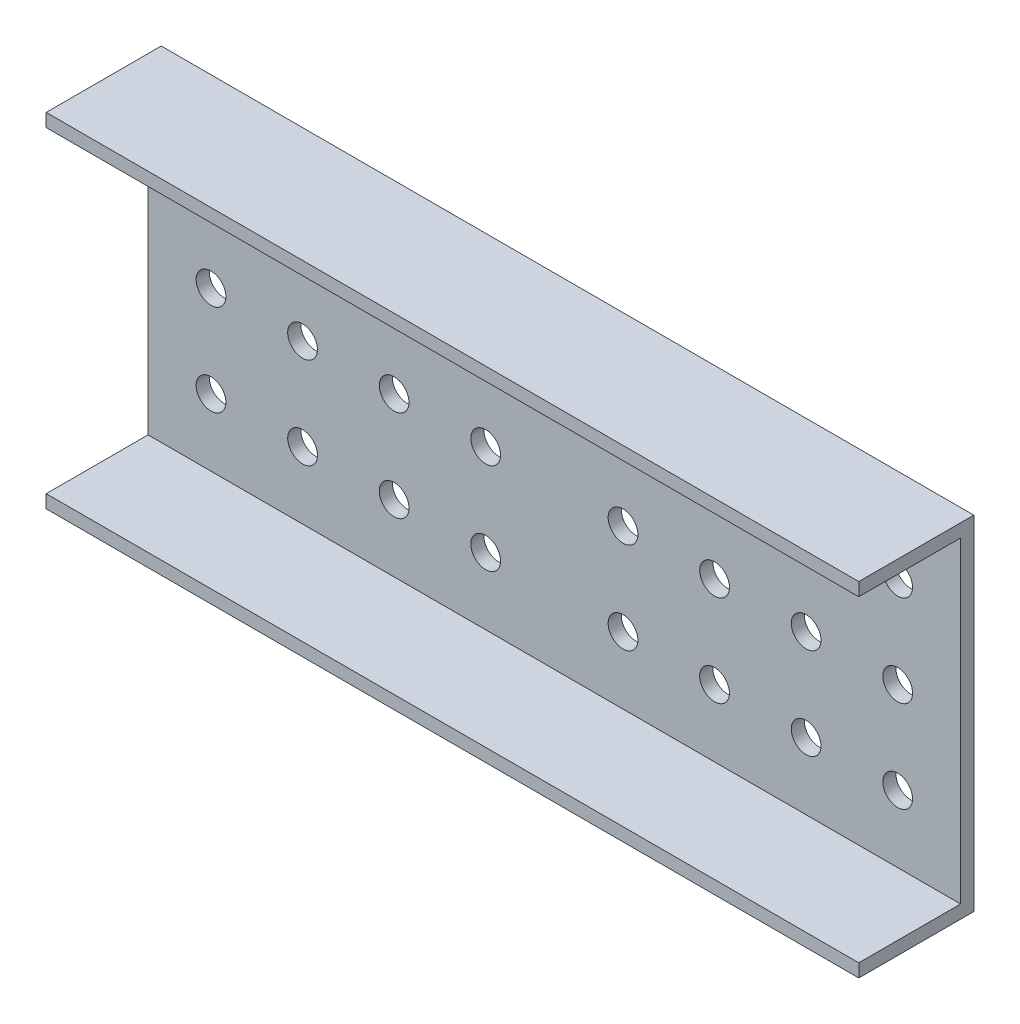
SolidWorks part; units mm, degrees
ref_plane "前视基准面" through (0, 0, 0) normal (0, 0, 1) x (1, 0, 0)
ref_plane "上视基准面" through (0, 0, 0) normal (0, 1, 0) x (1, 0, 0)
ref_plane "右视基准面" through (0, 0, 0) normal (1, 0, 0) x (0, 0, -1)
sketch "草图1" plane through (0, 0, 0) normal (0, 0, 1) x (1, 0, 0)
  line L1 (-355, 150) -> (355, 150)
  line L2 (-355, 150) -> (-355, -150)
  line L3 (-355, -150) -> (355, -150)
  line L4 (355, 150) -> (355, -150)
  line L5 (-355, 150) -> (355, -150) construction
  line L6 (-355, -150) -> (355, 150) construction
  point P0 (0, 0)
  dimension "D1" = 710
  dimension "D2" = 300
extrude "凸台-拉伸1" add sketch "草图1" along normal blind 11.5
sketch "草图2" plane through (0, 0, 11.5) normal (0, 0, 1) x (1, 0, 0)
  line L0 (-300, 150) -> (-300, -150) construction
  line L1 (355, 150) -> (-355, 150) construction
  line L2 (-355, -150) -> (355, -150) construction
  line L3 (-355, 150) -> (-355, -150) construction
  line L4 (-355, 80) -> (355, 80) construction
  line L5 (355, -150) -> (355, 150) construction
  line L6 (60, 150) -> (60, -150) construction
  circle A0 centre (-300, 80) radius 13
  circle A1 centre (60, 80) radius 13
  point P14 (-300, 80)
  point P15 (60, 80)
  dimension "D4" = 26
  dimension "D5" = 26
  dimension "D1" = 55
  dimension "D2" = 70
  dimension "D3" = 415
extrude "切除-拉伸1" cut sketch "草图2" against normal through all
pattern_linear "阵列(线性)1" count 4 spacing 80 along (1, 0, 0) count 3 spacing 80 along (0, -1, 0) of "切除-拉伸1"
sketch "草图3" plane through (0, 0, 11.5) normal (0, 0, 1) x (1, 0, 0)
  line L0 (-355, 138.5) -> (355, 138.5)
  line L1 (-355, 150) -> (-355, -150) construction
  line L2 (355, -150) -> (355, 150) construction
  line L3 (355, 150) -> (-355, 150) construction
  line L8 (355, -150) -> (355, 150)
  line L9 (355, 150) -> (-355, 150)
  line L10 (-355, 150) -> (-355, -150)
  line L11 (-355, -150) -> (355, -150)
  line L12 (355, 138.5) -> (355, 150)
  line L13 (355, 150) -> (-355, 150)
  line L14 (-355, 150) -> (-355, 138.5)
  dimension "D1" = 11.5
  dimension "D2" = 0
extrude "凸台-拉伸2" add sketch "草图3" along normal blind 89
mirror "镜向1" about plane through (0, 0, 0) normal (0, 1, 0) of "凸台-拉伸2"
